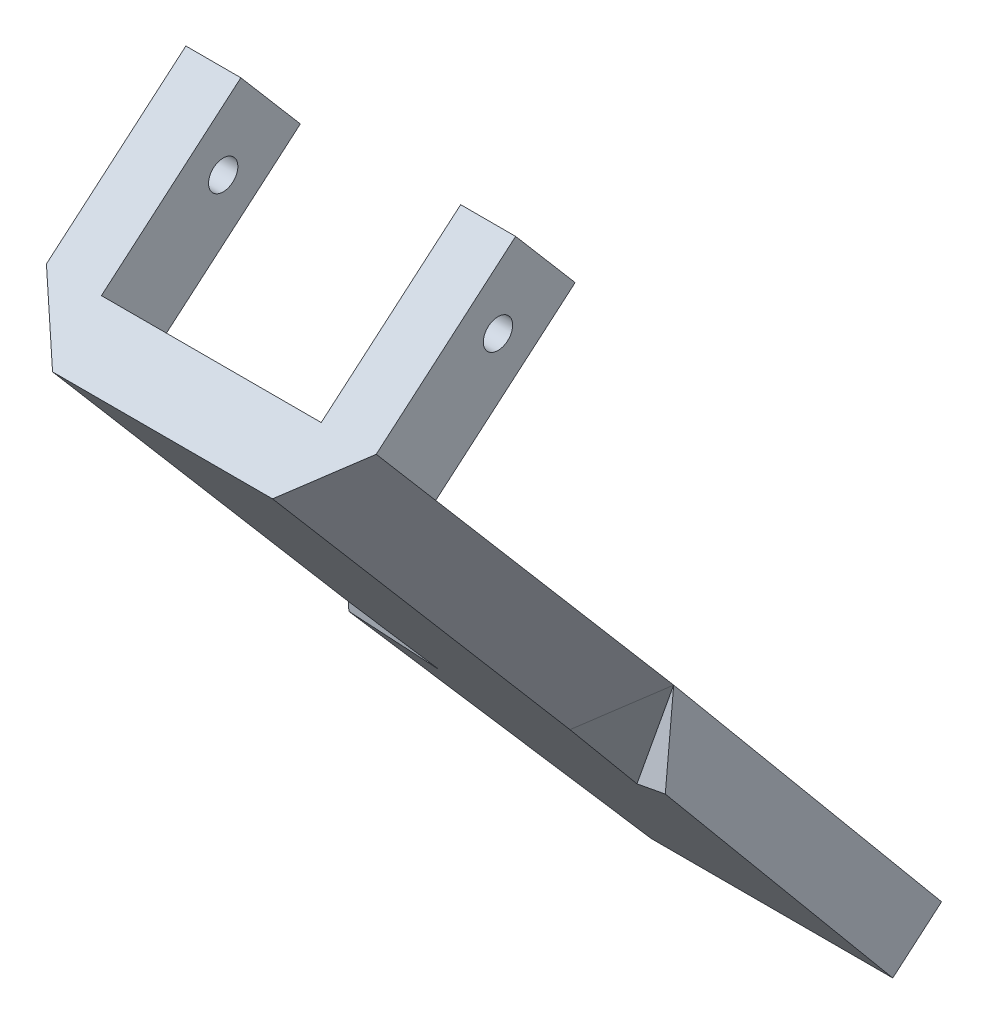
SolidWorks part; units mm, degrees
ref_plane "Front Plane" through (0, 0, 0) normal (0, 0, 1) x (1, 0, 0)
ref_plane "Top Plane" through (0, 0, 0) normal (0, 1, 0) x (1, 0, 0)
ref_plane "Right Plane" through (0, 0, 0) normal (1, 0, 0) x (0, 0, -1)
sketch "Sketch2" plane through (0, 56.2791, -65.9586) normal (0, -0.6491, 0.7607) x (1, 0, 0)
  line L0 (-16.7267, 3.2269) -> (-22.8499, 69.8597)
  line L1 (-22.8499, 69.8597) -> (22.8499, 69.8597)
  line L2 (22.8499, 69.8597) -> (16.7267, 3.2269)
  line L3 (16.7267, 3.2269) -> (-16.7267, 3.2269)
extrude "Boss-Extrude1" add sketch "Sketch2" along normal blind 8.89
sketch "Sketch3" plane through (0, 50.5088, -59.1958) normal (0, -0.6491, 0.7607) x (1, 0, 0)
  line L0 (22.8499, 69.8597) -> (-22.8499, 69.8597) construction
  line L1 (-15.24, 69.8597) -> (15.24, 69.8597)
  line L2 (-15.24, 69.8597) -> (-15.24, 3.2269)
  line L3 (-15.24, 3.2269) -> (15.24, 3.2269)
  line L4 (15.24, 69.8597) -> (15.24, 3.2269)
  line L5 (-16.7267, 3.2269) -> (16.7267, 3.2269) construction
  dimension "D1" = 30.48
  dimension "D2" = 15.24
ref_plane "Plane1" through (33.1902, 20.7613, -19.6331) normal (-0.7578, -0.474, 0.4483) x (0.4858, 0.0487, 0.8727)
sketch "Sketch9" plane through (33.1902, 20.7613, -19.6331) normal (-0.7578, -0.474, 0.4483) x (0.4858, 0.0487, 0.8727)
  line L0 (-54.6576, 42.1587) -> (-39.851, 28.8833) construction
  line L1 (-23.7613, 102.1651) -> (14.3387, 102.1651)
  line L2 (-23.7613, 102.1651) -> (-23.7613, -19.7023)
  line L3 (-23.7613, -19.7023) -> (14.3387, -19.7023)
  line L4 (14.3387, 102.1651) -> (14.3387, -19.7023)
  dimension "D1" = 38.1
extrude "Cut-Extrude1" cut sketch "Sketch9" along normal blind 10.16
sketch "Sketch10" plane through (0, 50.5088, -59.1958) normal (0, -0.6491, 0.7607) x (1, 0, 0)
  line L0 (0, 69.8597) -> (0, 3.2269) construction
  line L1 (-15.24, 69.8597) -> (15.24, 69.8597) construction
  line L2 (-15.24, 3.2269) -> (15.24, 3.2269) construction
ref_plane "Plane4" through (0, 0, 0) normal (-1, 0, 0) x (0, 0, 1)
mirror "Mirror1" about plane through (0, 0, 0) normal (-1, 0, 0) of "Cut-Extrude1"
sketch "Sketch11" plane through (0, 53.1436, 45.3447) normal (0, 0.7607, 0.6491) x (1, 0, 0)
  line L0 (-22.8499, 86.7057) -> (-15.24, 77.8157)
  line L1 (-15.24, 77.8157) -> (15.24, 77.8157)
  line L2 (15.24, 77.8157) -> (22.8499, 86.7057)
  line L3 (22.8499, 86.7057) -> (-22.8499, 86.7057)
extrude "Boss-Extrude2" add sketch "Sketch11" along normal blind 63.5
sketch "Sketch12" plane through (0, 56.2791, -65.9586) normal (0, 0.6491, -0.7607) x (-1, 0, 0)
  line L1 (-22.8499, 133.3597) -> (-15.2299, 133.3597)
  line L2 (-22.8499, 133.3597) -> (-22.8499, 120.6597)
  line L3 (-22.8499, 120.6597) -> (-15.2299, 120.6597)
  line L4 (-15.2299, 133.3597) -> (-15.2299, 120.6597)
  dimension "D1" = 12.7
  dimension "D2" = 7.62
extrude "Boss-Extrude3" add sketch "Sketch12" along normal blind 25.4 contours L4 L3 L2 L1
ref_plane "Plane5" through (0, 0, 0) normal (1, 0, 0) x (0, 0, -1)
mirror "Mirror2" about plane through (0, 0, 0) normal (1, 0, 0) of "Boss-Extrude3"
sketch "Sketch13" plane through (-22.8499, 0, 0) normal (-1, 0, 0) x (0, 0, 1)
  line L0 (1.2806, 174.215) -> (20.6029, 157.7283) construction
  line L2 (20.6029, 157.7283) -> (12.3595, 148.0672) construction
  circle A0 centre (3.7285, 163.7789) radius 2.032
  dimension "D1" = 4.064
  dimension "D2" = 6.35
  dimension "D3" = 16.764
extrude "Cut-Extrude2" cut sketch "Sketch13" against normal through all
